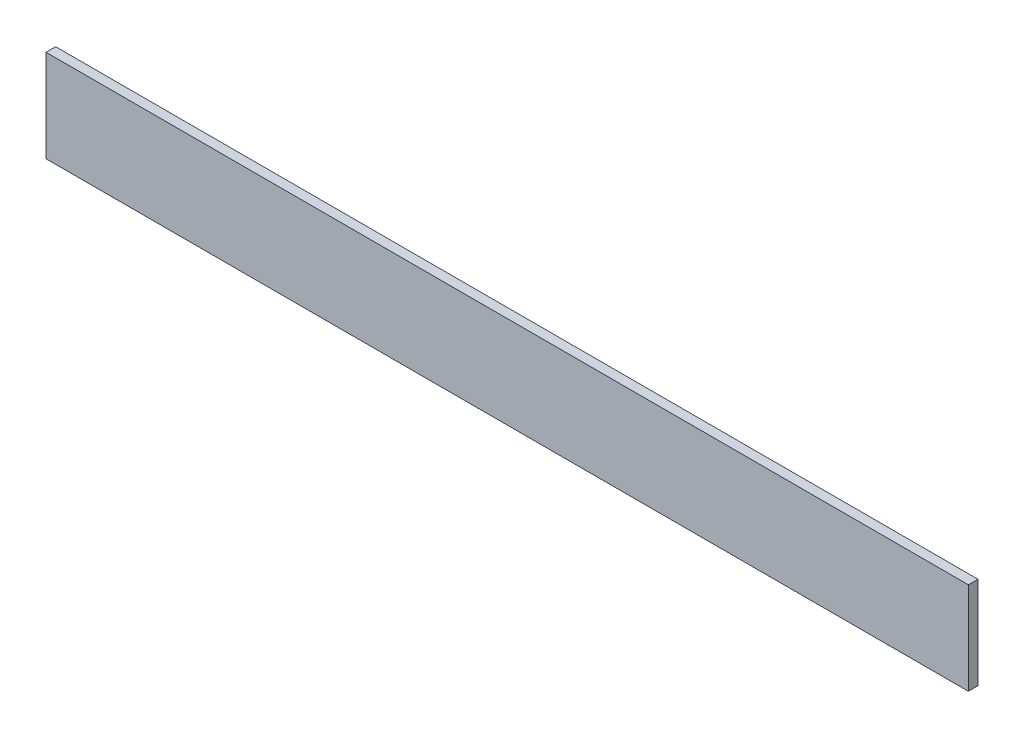
SolidWorks part; units mm, degrees
ref_plane "前视基准面" through (0, 0, 0) normal (0, 0, 1) x (1, 0, 0)
ref_plane "上视基准面" through (0, 0, 0) normal (0, 1, 0) x (1, 0, 0)
ref_plane "右视基准面" through (0, 0, 0) normal (1, 0, 0) x (0, 0, -1)
sketch "草图1" plane through (0, 0, 0) normal (0, 1, 0) x (1, 0, 0)
  line L1 (0, 0) -> (10000, 0)
  line L2 (0, 0) -> (0, -104.4469)
  line L3 (0, -104.4469) -> (10000, -104.4469)
  line L4 (10000, 0) -> (10000, -104.4469)
  dimension "D1" = 10000
extrude "凸台-拉伸1" add sketch "草图1" along normal blind 1000
